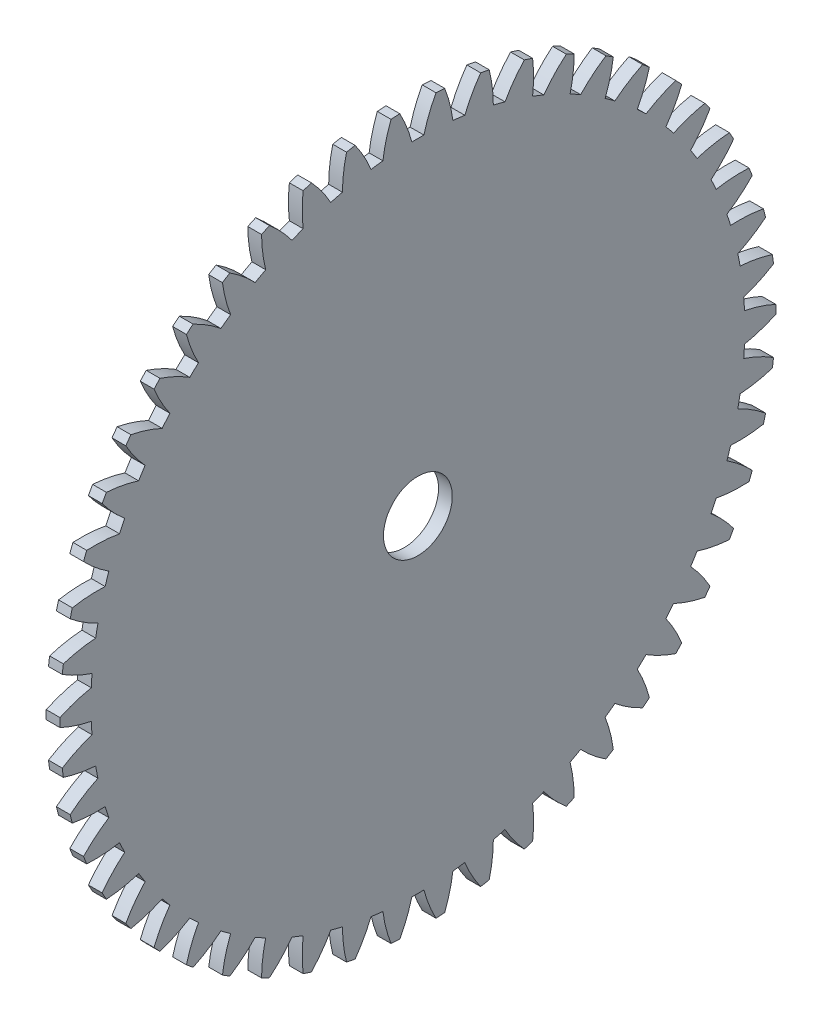
SolidWorks part; units mm, degrees
ref_plane "Plane1" through (0, 0, 0) normal (0, 0, 1) x (1, 0, 0)
ref_plane "Plane2" through (0, 0, 0) normal (0, 1, 0) x (1, 0, 0)
ref_plane "Plane3" through (0, 0, 0) normal (1, 0, 0) x (0, 0, -1)
sketch "HoldingSke" plane through (0, 0, 0) normal (0, 1, 0) x (1, 0, 0)
  line L0 (0, 0) -> (0.6428, -0.766)
  line L1 (-15, 0) -> (100, 0) construction
  line L2 (0, 0) -> (-2.1039, 2.3779)
  line L3 (0, 0) -> (-11.863, 4.5341)
  line L4 (0, 0) -> (5.5511, 6.6156)
  line L5 (0, 0) -> (-46.8476, -17.4728)
  line L6 (0, 0) -> (-0.829, -0.5593)
  line L7 (-2.1039, 2.3779) -> (8.6586, 51.2059)
  line L8 (-76.2, 54.61) -> (-75.3, 54.61)
  line L9 (-71.009, 38.7566) -> (-53.1078, 45.2721)
  line L10 (-76.2, 71.12) -> (104.1128, 71.12)
  line L11 (0, 0) -> (-1, 0)
  line L12 (-76.2, 101.6) -> (-76.162, 101.6)
  line L13 (24.9733, 27.94) -> (52.9518, 28.4284)
  line L14 (24.9733, 27.94) -> (24.9743, 27.94)
  line L15 (24.9733, 27.94) -> (100.4006, 29.5858)
  line L16 (-63.627, -1) -> (-12.827, -1)
  circle A0 centre (0, 0) radius 2.5
  circle A1 centre (0, 0) radius 23.749
  circle A2 centre (0, 0) radius 37.5
  circle A3 centre (0, 0) radius 2.5
  dimension "MHD" = 47.498
  dimension "Hub_dia" = 75
  dimension "Bore" = 5
  dimension "MBD" = 5
  dimension "Num_teeth" = 50
  dimension "Pitch" = 1
  dimension "Overall_len" = 50
  dimension "Show_teeth" = 50
  dimension "Thickness" = 1
  dimension "OAL" = 50.0001
  dimension "T_dim" = 0.9
  dimension "Ap" = 20
  dimension "H" = 19.05
  dimension "Pitch_radius" = 180.3128
  dimension "Width" = 1
  dimension "Backlash" = 0.038
  dimension "Addendum_fac" = 1
  dimension "Dedendum_fac" = 1.25
  dimension "Clearance_fac" = 0.25
  dimension "Dedendum_add" = 0.001
  dimension "Module" = 1
sketch "BasProSke" plane through (0, 0, 0) normal (0, 1, 0) x (1, 0, 0)
  line L0 (-10, 0) -> (60, 0) construction
  line L1 (0, 0) -> (0, 26)
  line L2 (0, 0) -> (1, 0)
  line L3 (1, 0) -> (1, 26)
  line L4 (1, 26) -> (0, 26)
  dimension "Thickness" = 1
  dimension "Diameter" = 52
revolve "Base-Revolve" add sketch "BasProSke" angle 360 about L0
sketch "TooCutSke" plane through (0, 0, 0) normal (1, 0, 0) x (0, 0, -1)
  line L1 (0, 0) -> (0, 107) construction
  line L2 (0, 0) -> (-0.8518, 24.9855) construction
  line L3 (0, 0) -> (-3.1382, 49.8807) construction
  line L4 (-0.8518, 24.9855) -> (-1.5691, 24.9404) construction
  arc A0 (0.4377, 23.745) -> (-0.4377, 23.745) centre (0, 0) ccw
  arc A1 (1.3294, 25.9914) -> (-1.3294, 25.9914) centre (0, 0) ccw
  circle A2 centre (0, 0) radius 25 construction
  circle A3 centre (0, 0) radius 23.4923 construction
  arc A4 (-0.4377, 23.745) -> (-1.3294, 25.9914) centre (-10.1099, 21.2056) ccw
  arc A5 (1.3294, 25.9914) -> (0.4377, 23.745) centre (10.1099, 21.2056) ccw
  dimension "Root_dia" = 47.498
  dimension "Overcut_dia" = 52.0508
  dimension "Pitch_dia" = 50
  dimension "Base_dia" = 46.9846
  dimension "Flank_rad" = 10
  dimension "Half_ang" = 3.6
  dimension "Half_CT" = 0.7188
extrude "ToothCut" cut sketch "TooCutSke" along normal through all
fillet "Breaks" [suppressed] radius 0.02
fillet "RootFillets" [suppressed] radius 0.251
pattern_circular "TeethCuts" count 50 every 7.2 about axis through (-10, 0, 0) along (1, 0, 0) of "ToothCut", "RootFillets", "Breaks"
sketch "HubNeaOneSke" plane through (0, 0, 0) normal (-1, 0, 0) x (0, 0, 1)
  circle A0 centre (0, 0) radius 23.749
  dimension "Diameter" = 47.498
extrude "HubNearOne" [suppressed] add sketch "HubNeaOneSke" along normal blind 49.0001
sketch "HubNeaBotSke" plane through (0, 0, 0) normal (-1, 0, 0) x (0, 0, 1)
  circle A0 centre (0, 0) radius 23.749
  dimension "Diameter" = 47.498
extrude "HubNearBoth" [suppressed] add sketch "HubNeaBotSke" along normal blind 24.5
ref_plane "FarPln" through (1, 0, 0) normal (1, 0, 0) x (0, 0, -1)
sketch "HubFarSke" plane through (1, 0, 0) normal (1, 0, 0) x (0, 0, -1)
  circle A0 centre (0, 0) radius 23.749
  dimension "Diameter" = 47.498
extrude "HubFar" [suppressed] add sketch "HubFarSke" along normal blind 24.5
sketch "BorSke" plane through (0, 0, 0) normal (1, 0, 0) x (0, 0, -1)
  circle A0 centre (0, 0) radius 2.5
  dimension "Diameter" = 5
extrude "Bore" cut sketch "BorSke" along normal mid plane 100.0001
sketch "KeySke" plane through (0, 0, 0) normal (1, 0, 0) x (0, 0, -1)
  line L0 (-1, 0) -> (-1, 3.4)
  line L1 (-1, 3.4) -> (1, 3.4)
  line L2 (1, 3.4) -> (1, 0)
  line L3 (0, 0) -> (0, 34) construction
  line L4 (-1, 0) -> (1, 0)
  dimension "Offset" = 3.4
  dimension "Width" = 2
extrude "Keyway" [suppressed] cut sketch "KeySke" along normal mid plane 100.0001
pattern_circular "Keyway2" [suppressed] count 2 every 90 about axis through (-10, 0, 0) along (1, 0, 0)
equation "' \"Module@HoldingSke\" = 6.35"
equation "' \"Num_teeth@HoldingSke\" = 12"
equation "' \"Ap@HoldingSke\" =  20"
equation "' \"Ap@HoldingSke\" = 20"
equation "' \"Width@HoldingSke\" = 0.5 * 25.4"
equation "' \"Hub_dia@HoldingSke\"= 1 * 25.4"
equation "' \"Hub_dia@HoldingSke\" = 1 * 25.4"
equation "' \"Overall_len@HoldingSke\" = 1.0 * 25.4"
equation "' \"Bore@HoldingSke\" = 0.75 * 25.4"
equation "' \"T_dim@HoldingSke\" = 0.1 * 25.4"
equation "' \"Width@KeySke\" = 0.25 * 25.4"
equation "' \"Show_teeth@HoldingSke\" = 13"
equation "' \"Backlash@HoldingSke\" = 0.009 * 25.4"
equation "' \"Addendum_fac@HoldingSke\" = 1.0"
equation "' \"Dedendum_fac@HoldingSke\" = 1.25"
equation "' \"Dedendum_add@HoldingSke\" = 0.00005 * 25.4"
equation "' \"Clearance_fac@HoldingSke\" = 0.25"
equation "\"Pitch@HoldingSke\" = 1 / \"Module@HoldingSke\""
equation "\"Overcut_dia@TooCutSke\" = (\"Num_teeth@HoldingSke\" + 2 * \"Addendum_fac@HoldingSke\") / \"Pitch@HoldingSke\" + 0.002 * 25.4"
equation "\"Pitch_dia@TooCutSke\" = \"Num_teeth@HoldingSke\" / \"Pitch@HoldingSke\""
equation "\"Base_dia@TooCutSke\" = \"Num_teeth@HoldingSke\" / \"Pitch@HoldingSke\" * cos((\"Ap@HoldingSke\"  * 3.14159265 / 180))"
equation "\"Root_dia@TooCutSke\" = (\"Num_teeth@HoldingSke\" + 2) / \"Pitch@HoldingSke\" - 2 * (\"Addendum_fac@HoldingSke\" + \"Dedendum_fac@HoldingSke\") / \"Pitch@HoldingSke\" - \"Dedendum_add@HoldingSke\" * 2"
equation "\"Half_ang@TooCutSke\" = 180 / \"Num_teeth@HoldingSke\""
equation "\"Half_CT@TooCutSke\" = \"Num_teeth@HoldingSke\" / \"Pitch@HoldingSke\" * sin((3.14159265 / 2 / \"Num_teeth@HoldingSke\")) / 2 - 7 * \"Backlash@HoldingSke\" / 4"
equation "\"Flank_rad@TooCutSke\" = \"Num_teeth@HoldingSke\" / \"Pitch@HoldingSke\" / 5"
equation "\"Radius@RootFillets\" = \"Clearance_fac@HoldingSke\" / \"Pitch@HoldingSke\" + \"Dedendum_add@HoldingSke\""
equation "\"Break_rad@Breaks\" = 0.02 / \"Pitch@HoldingSke\""
equation "\"Thickness@HoldingSke\" = \"Width@HoldingSke\""
equation "\"OAL@HoldingSke\" = \"Thickness@HoldingSke\""
equation "\"MHD@HoldingSke\" = (\"Num_teeth@HoldingSke\" + 2) / \"Pitch@HoldingSke\" - 2 * (\"Addendum_fac@HoldingSke\" + \"Dedendum_fac@HoldingSke\")  / \"Pitch@HoldingSke\" - \"Dedendum_add@HoldingSke\" * 2"
equation "\"MBD@HoldingSke\" = (\"Num_teeth@HoldingSke\" + 2) / \"Pitch@HoldingSke\" - 2 * (\"Addendum_fac@HoldingSke\" + \"Dedendum_fac@HoldingSke\")  / \"Pitch@HoldingSke\" - \"Dedendum_add@HoldingSke\" * 2 - 0.002 * 25.4"
equation "\"MHD@HoldingSke\" = ((sgn( \"MHD@HoldingSke\" - \"Hub_dia@HoldingSke\" )-1)*( \"MHD@HoldingSke\" - \"Hub_dia@HoldingSke\" ))/-2+ \"Hub_dia@HoldingSke\""
equation "\"MBD@HoldingSke\" = ((sgn( \"MBD@HoldingSke\" - \"Bore@HoldingSke\" )-1)*( \"MBD@HoldingSke\" - \"Bore@HoldingSke\" ))/-2+ \"Bore@HoldingSke\""
equation "\"OAL@HoldingSke\" = ((sgn( \"OAL@HoldingSke\" - \"Overall_len@HoldingSke\" )+1)*( \"OAL@HoldingSke\" - \"Overall_len@HoldingSke\" ))/2 + \"Overall_len@HoldingSke\" + 0.000002 * 25.4"
equation "\"Num_teeth@TeethCuts\" = int( \"Show_teeth@HoldingSke\" ) + 1"
equation "\"Num_teeth@TeethCuts\" = ((sgn( \"Num_teeth@TeethCuts\" - \"Num_teeth@HoldingSke\" )-1)*( \"Num_teeth@TeethCuts\" - \"Num_teeth@HoldingSke\" ))/-2+ \"Num_teeth@HoldingSke\""
equation "\"Num_teeth@TeethCuts\" = ((sgn( \"Num_teeth@TeethCuts\" - 2.0)+1)*( \"Num_teeth@TeethCuts\" - 2.0))/2 +2.0"
equation "\"Angle@TeethCuts\" = 360.0 / \"Num_teeth@HoldingSke\""
equation "\"Diameter@BasProSke\" = (\"Num_teeth@HoldingSke\" + 2 * \"Addendum_fac@HoldingSke\") / \"Pitch@HoldingSke\""
equation "\"Thickness@BasProSke\"  = \"Thickness@HoldingSke\""
equation "' \"Fillet_rad@BasProSke\" =  \"Thickness@HoldingSke\" * 0.05"
equation "' \"Fillet_rad@BasProSke\" = \"Thickness@HoldingSke\" * 0.05"
equation "\"MHD@HoldingSke\" = ((sgn( \"MHD@HoldingSke\" - \"Root_dia@TooCutSke\" )-1)*( \"MHD@HoldingSke\" - \"Root_dia@TooCutSke\" ))/-2+ \"Root_dia@TooCutSke\""
equation "\"Diameter@HubNeaOneSke\" = \"MHD@HoldingSke\""
equation "\"Length@HubNearOne\" = \"OAL@HoldingSke\" - \"Thickness@BasProSke\""
equation "\"Diameter@HubNeaBotSke\" = \"MHD@HoldingSke\""
equation "\"Length@HubNearBoth\" = ( \"OAL@HoldingSke\" - \"Thickness@BasProSke\" ) / 2.0"
equation "\"Thickness@FarPln\" = \"Thickness@BasProSke\""
equation "\"Diameter@HubFarSke\" = \"MHD@HoldingSke\""
equation "\"Length@HubFar\" = ( \"OAL@HoldingSke\" - \"Thickness@BasProSke\" ) / 2.0"
equation "\"Diameter@BorSke\" = \"MBD@HoldingSke\""
equation "\"D1@Bore\" = \"OAL@HoldingSke\" * 2.0"
equation "\"D1@Keyway\" = \"OAL@HoldingSke\" * 2.0"
equation "\"Offset@KeySke\" = \"T_dim@HoldingSke\" + \"MBD@HoldingSke\" / 2.0"
